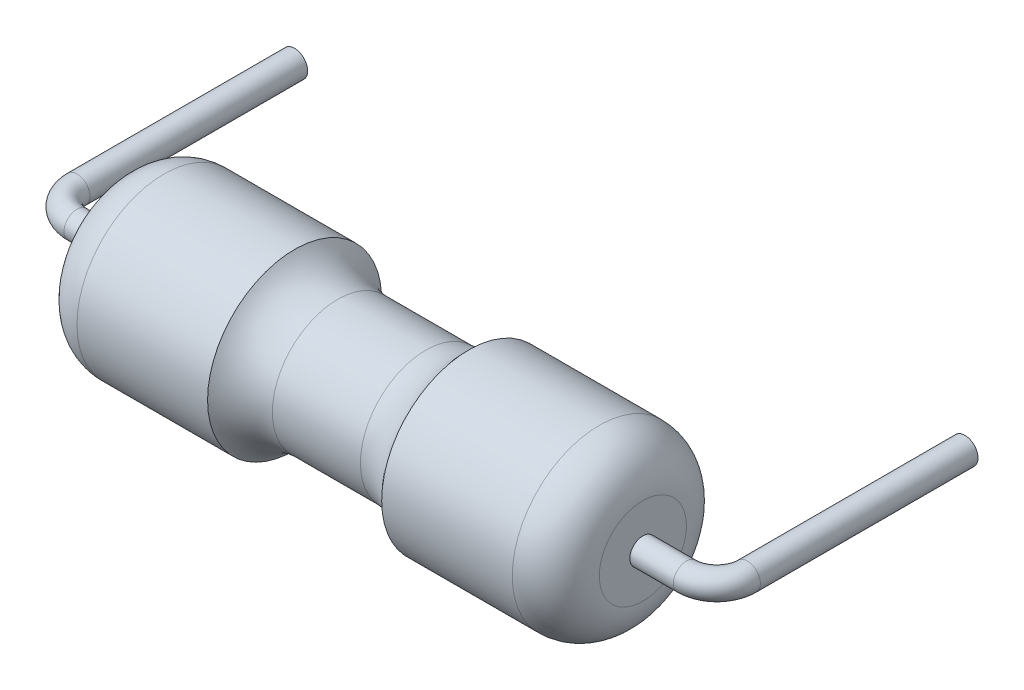
SolidWorks part; units mm, degrees
ref_plane "前视基准面" through (0, 0, 0) normal (0, 0, 1) x (1, 0, 0)
ref_plane "上视基准面" through (0, 0, 0) normal (0, 1, 0) x (1, 0, 0)
ref_plane "右视基准面" through (0, 0, 0) normal (1, 0, 0) x (0, 0, -1)
sketch "草图1" plane through (0, 0, 0) normal (0, 0, 1) x (1, 0, 0)
  line L0 (-1000, 0) -> (49000, 0) construction
  line L1 (3, 0.5) -> (3, 0)
  line L2 (0, -1000) -> (0, 49000) construction
  line L3 (2.5, 1) -> (1, 1)
  line L4 (-0.5056, 0.75) -> (0.5056, 0.75)
  line L5 (-3, 0) -> (3, 0)
  line L6 (-3, 0.5) -> (-3, 0)
  line L7 (-2.5, 1) -> (-1, 1)
  line L9 (2, 1.1381) -> (2, 0.3092) construction
  arc A0 (-2.5, 1) -> (-3, 0.5) centre (-2.5, 0.5) ccw
  arc A1 (2.5, 1) -> (3, 0.5) centre (2.5, 0.5) cw
  arc A2 (-1, 1) -> (-0.5056, 0.75) centre (-0.4881, 1.3985) ccw
  arc A3 (1, 1) -> (0.5056, 0.75) centre (0.4881, 1.3985) cw
  point P15 (-3, 1)
  dimension "D5" = 0.5
  dimension "D1" = 6
  dimension "D2" = 2
  dimension "D3" = 1.5
revolve "旋转1" add sketch "草图1" angle 360 about L0
sketch "草图2" plane through (3, 0, 0) normal (1, 0, 0) x (0, 0, -1)
  circle A0 centre (0, 0) radius 0.15
sketch "草图3" plane through (0, 0, 0) normal (0, 1, 0) x (1, 0, 0)
  line L0 (-997, 0) -> (49003, 0) construction
  line L1 (3, -0.15) -> (3, 0.15) construction
  line L2 (3.6696, -0.15) -> (2.8513, -0.15) construction
  line L3 (3, 0) -> (3, -0.3888) construction
  line L4 (3, -0.5) -> (3, 0.5) construction
  line L5 (3, -0.15) -> (3.5, -0.15)
  line L6 (4, 0.35) -> (4, 2.85)
  arc A0 (4, 0.35) -> (3.5, -0.15) centre (3.5, 0.35) cw
  point P5 (3, 0)
  point P16 (4, -0.15)
  dimension "D4" = 0.5
  dimension "D1" = 0.15
  dimension "D2" = 1
  dimension "D3" = 3
sweep "扫描1" add profiles "草图2" path "草图3"
mirror "镜向1" about plane through (0, 0, 0) normal (1, 0, 0) of "扫描1"
